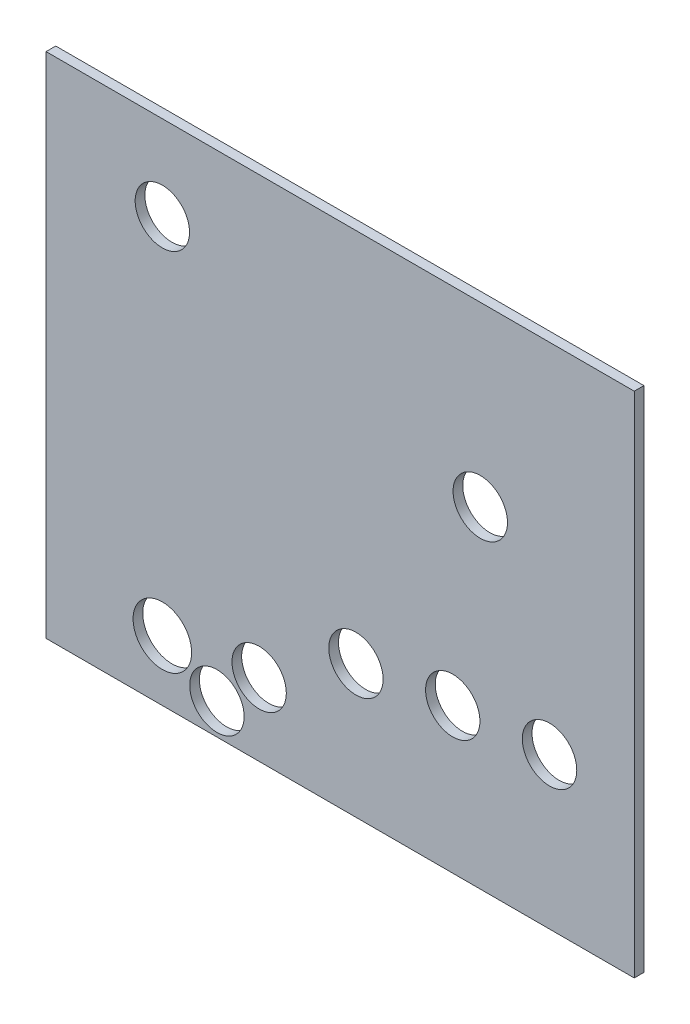
SolidWorks part; units mm, degrees
ref_plane "Front Plane" through (0, 0, 0) normal (0, 0, 1) x (1, 0, 0)
ref_plane "Top Plane" through (0, 0, 0) normal (0, 1, 0) x (1, 0, 0)
ref_plane "Right Plane" through (0, 0, 0) normal (1, 0, 0) x (0, 0, -1)
sketch "Sketch1" plane through (0, 0, 0) normal (0, 0, 1) x (1, 0, 0)
  line L8 (80.8024, 92.9856) -> (-227.8685, 92.9856)
  line L9 (-227.8685, 92.9856) -> (-227.8685, -173.7144)
  line L14 (-227.8685, -173.7144) -> (80.8024, -173.7144)
  line L15 (80.8024, -173.7144) -> (80.8024, 92.9856)
  circle A0 centre (0, 0) radius 14.2875
  circle A1 centre (-138.2019, -157.325) radius 14.2875
  circle A13 centre (-166.8476, 48.5356) radius 14.2621
  circle A14 centre (-166.8476, -141.9644) radius 15.3659
  circle A15 centre (-116.0476, -135.6144) radius 14.2621
  circle A16 centre (-65.2476, -103.8644) radius 14.2621
  circle A17 centre (-14.4476, -97.5144) radius 14.2621
  circle A19 centre (36.3524, -94.3893) radius 14.2875
  point P5 (0, 0)
  point P6 (0, 0)
extrude "Boss-Extrude1" add sketch "Sketch1" along normal blind 5.08
